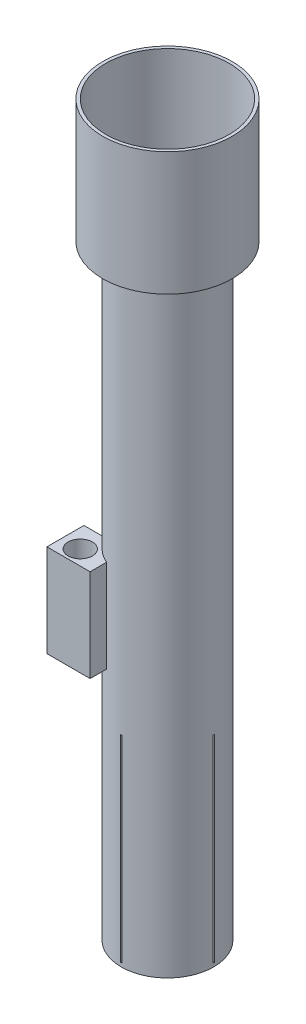
SolidWorks part; units mm, degrees
material "ABS"
ref_plane "Front Plane" through (0, 0, 0) normal (0, 0, 1) x (1, 0, 0)
ref_plane "Top Plane" through (0, 0, 0) normal (0, 1, 0) x (1, 0, 0)
ref_plane "Right Plane" through (0, 0, 0) normal (1, 0, 0) x (0, 0, -1)
sketch "Sketch1" plane through (0, 0, 0) normal (0, 1, 0) x (1, 0, 0)
  circle A0 centre (0, 0) radius 9.525
  dimension "D1" = 19.05
extrude "Boss-Extrude1" add sketch "Sketch1" along normal blind 150
sketch "Sketch2" plane through (0, 150, 0) normal (0, 1, 0) x (1, 0, 0)
  circle A0 centre (0, 0) radius 9.144
  dimension "D1" = 18.288
extrude "Cut-Extrude1" cut sketch "Sketch2" against normal blind 177.8
sketch "Sketch3" plane through (0, 0, 0) normal (1, 0, 0) x (0, 0, -1)
  line L0 (0, -7.4747) -> (0, 0) construction
  line L1 (-0.127, 0.762) -> (0.127, 0.762)
  line L2 (0.127, 0.762) -> (0.127, 41.402)
  line L3 (0.127, 41.402) -> (-0.127, 41.402)
  line L4 (-0.127, 41.402) -> (-0.127, 0.762)
  line L5 (0, 0) -> (0, 0.762) construction
  dimension "D1" = 40.64
  dimension "D2" = 0.254
  dimension "D3" = 0.762
extrude "Cut-Extrude3" cut sketch "Sketch3" against normal blind 1.27 from offset 10.16
sketch "Sketch4" plane through (0, 0, 0) normal (0, 0, 1) x (1, 0, 0)
  line L0 (0, 0) -> (0, 2.54) construction
  line L1 (0, 2.54) -> (0.254, 2.54)
  line L2 (0.254, 2.54) -> (0.254, 53.34)
  line L3 (0.254, 53.34) -> (0, 53.34)
  line L4 (0, 53.34) -> (0, 2.54)
  dimension "D1" = 2.54
  dimension "D2" = 50.8
  dimension "D3" = 0.254
sketch "Sketch5" plane through (0, 150, 0) normal (0, 1, 0) x (1, 0, 0)
  circle A0 centre (0, 0) radius 12.7
  dimension "D1" = 25.4
sketch "Sketch8" plane through (0, 150, 0) normal (0, 1, 0) x (1, 0, 0)
  circle A0 centre (0, 0) radius 12.7
  dimension "D1" = 25.4
pattern_circular "CirPattern1" count 4 over 360 about axis through (0, 0, 0) along (0, 1, 0) of "Cut-Extrude3"
ref_plane "Plane1" through (0, 150, 0) normal (0, 1, 0) x (1, 0, 0)
sketch "Sketch9" plane through (0, 150, 0) normal (0, 1, 0) x (1, 0, 0)
  circle A0 centre (0, 0) radius 13.335
  dimension "D1" = 26.67
extrude "Boss-Extrude2" add sketch "Sketch9" against normal blind 25.4
sketch "Sketch10" plane through (0, 150, 0) normal (0, 1, 0) x (1, 0, 0)
  circle A0 centre (0, 0) radius 12.7
  dimension "D1" = 25.4
extrude "Cut-Extrude5" cut sketch "Sketch10" against normal blind 24.13
sketch "Sketch11" plane through (0, 124.6, 0) normal (0, -1, 0) x (1, 0, 0)
  circle A0 centre (0, 0) radius 9.144
extrude "Cut-Extrude6" cut sketch "Sketch11" against normal blind 24.13
sketch "Sketch12" plane through (0, 0, 0) normal (0, 1, 0) x (1, 0, 0)
  line L1 (-3.81, -12.115) -> (-12.7, -12.115)
  line L2 (-3.81, -12.115) -> (-3.81, -4.495)
  line L3 (-3.81, -4.495) -> (-12.7, -4.495)
  line L4 (-12.7, -12.115) -> (-12.7, -4.495)
  dimension "D1" = 12.7
  dimension "D2" = 8.89
  dimension "D3" = 7.62
  dimension "D4" = 12.7
extrude "Boss-Extrude3" add sketch "Sketch12" along normal blind 19.05 from offset 50.8
sketch "Sketch13" plane through (0, 69.85, 0) normal (0, 1, 0) x (1, 0, 0)
  line L0 (-12.7, -4.495) -> (-12.7, -12.115) construction
  line L1 (-12.7, -12.115) -> (-3.81, -12.115) construction
  circle A0 centre (-8.89, -9.067) radius 2.5
  dimension "D1" = 5
  dimension "D2" = 3.81
  dimension "D3" = 3.048
extrude "Cut-Extrude7" cut sketch "Sketch13" against normal blind 19.05
sketch "Sketch14" plane through (0, 0, 0) normal (0, 1, 0) x (1, 0, 0)
  circle A0 centre (0, 0) radius 9.144
extrude "Cut-Extrude8" cut sketch "Sketch14" along normal blind 60.96
